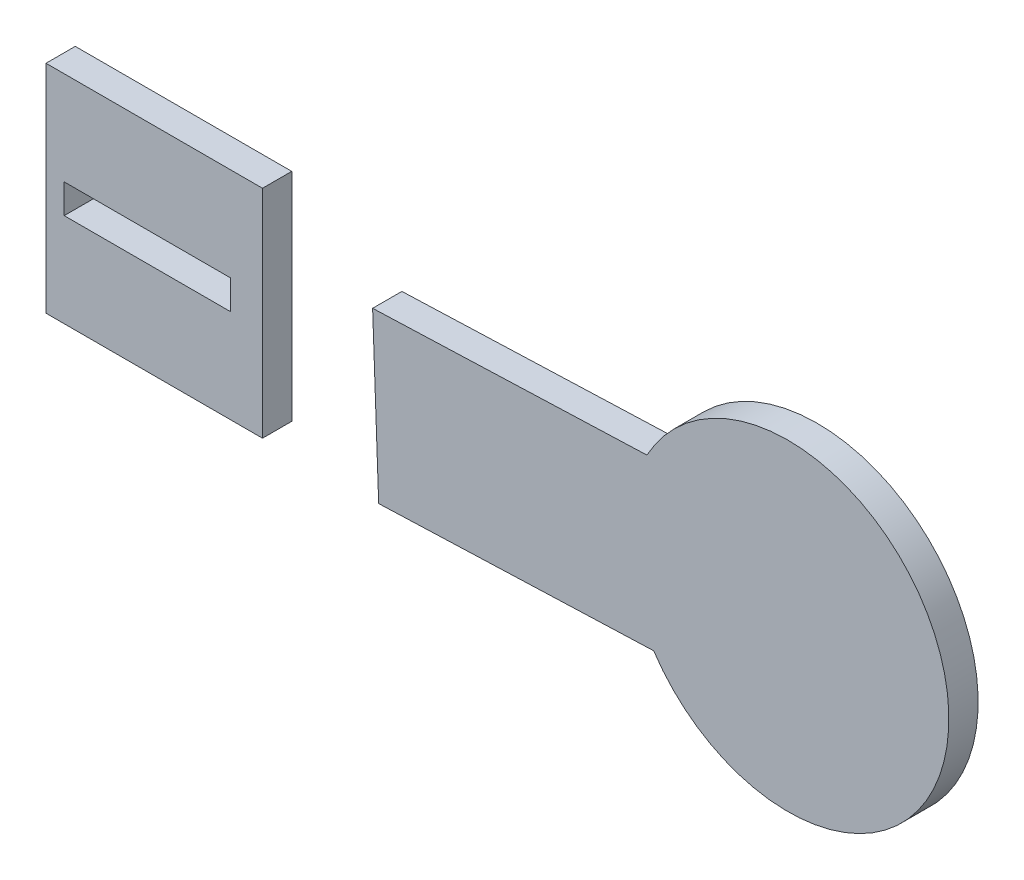
SolidWorks part; units mm, degrees
ref_plane "Plan de face" through (0, 0, 0) normal (0, 0, 1) x (1, 0, 0)
ref_plane "Plan de dessus" through (0, 0, 0) normal (0, 1, 0) x (1, 0, 0)
ref_plane "Plan de droite" through (0, 0, 0) normal (1, 0, 0) x (0, 0, -1)
sketch "Esquisse1" plane through (0, 0, 0) normal (0, 0, 1) x (1, 0, 0)
  circle A0 centre (-60.4073, 29.2187) radius 27.5
  dimension "D1" = 55
extrude "Boss.-Extru.1" add sketch "Esquisse1" along normal blind 5
sketch "Esquisse2" plane through (0, 0, 5) normal (0, 0, 1) x (1, 0, 0)
  line L0 (-83.3549, 14.0643) -> (-130.3549, 12.349)
  line L1 (-84.5152, 42.4498) -> (-131.391, 40.7391)
  line L2 (-130.3549, 12.349) -> (-131.391, 40.7391)
  line L4 (-150.2118, 12.0955) -> (-187.2118, 12.0955)
  line L5 (-150.2118, 12.0955) -> (-150.2118, 49.0955)
  line L6 (-150.2118, 49.0955) -> (-187.2118, 49.0955)
  line L7 (-187.2118, 12.0955) -> (-187.2118, 49.0955)
  line L8 (-155.7118, 28.0955) -> (-184.1018, 28.0955)
  line L9 (-155.7118, 28.0955) -> (-155.7118, 33.0955)
  line L10 (-155.7118, 33.0955) -> (-184.1018, 33.0955)
  line L11 (-184.1018, 28.0955) -> (-184.1018, 33.0955)
  circle A0 centre (-60.4073, 29.2187) radius 27.5 construction
  circle A2 centre (-60.4073, 29.2187) radius 27.5
  arc A3 (-83.3549, 14.0643) -> (-84.5152, 42.4498) centre (-60.4073, 29.2187) ccw
  point P16 (-155.7118, 30.5955)
  dimension "D1" = 0
  dimension "D2" = 47
  dimension "D3" = 37
  dimension "D4" = 37
  dimension "D5" = 16
  dimension "D6" = 5
  dimension "D7" = 5.5
  dimension "D8" = 28.3901
extrude "Boss.-Extru.2" add sketch "Esquisse2" against normal blind 5
